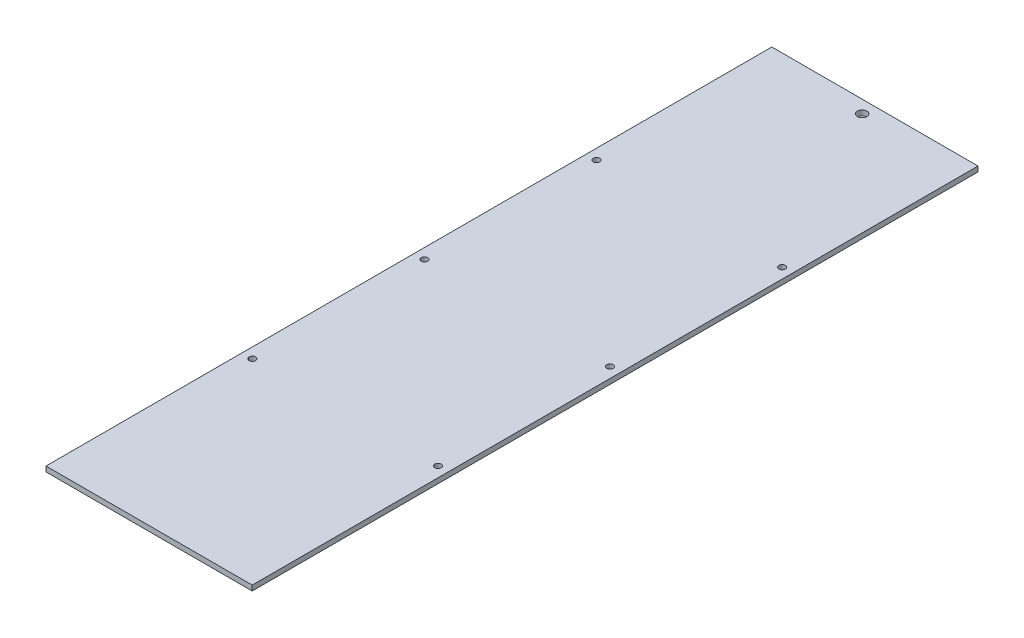
SolidWorks part; units mm, degrees
ref_plane "Front" through (0, 0, 0) normal (0, 0, 1) x (1, 0, 0)
ref_plane "Top" through (0, 0, 0) normal (0, 1, 0) x (1, 0, 0)
ref_plane "Right" through (0, 0, 0) normal (1, 0, 0) x (0, 0, -1)
sketch "Sketch1" plane through (0, 0, 0) normal (0, 1, 0) x (1, 0, 0)
  line L1 (-40, -140.81) -> (40, -140.81)
  line L2 (-40, -140.81) -> (-40, 140.81)
  line L3 (-40, 140.81) -> (40, 140.81)
  line L4 (40, -140.81) -> (40, 140.81)
  line L5 (-40, -140.81) -> (40, 140.81) construction
  line L6 (-40, 140.81) -> (40, -140.81) construction
  point P0 (0, 0)
  dimension "D1" = 281.62
  dimension "D2" = 80
extrude "Boss-Extrude1" add sketch "Sketch1" along normal blind 2
sketch "Sketch2" plane through (0, 2, 0) normal (0, 1, 0) x (1, 0, 0)
  line L0 (40, 140.81) -> (-40, 140.81) construction
  circle A0 centre (0, 135.87) radius 1.85
  dimension "D1" = 3.7
  dimension "D2" = 4.94
extrude "Cut-Extrude1" cut sketch "Sketch2" against normal blind 2
sketch "Sketch3" plane through (0, 2, 0) normal (0, 1, 0) x (1, 0, 0)
  line L0 (-40, 140.81) -> (-40, -140.81) construction
  line L1 (40, 140.81) -> (-40, 140.81) construction
  circle A0 centre (-36, 68.81) radius 1.25
  dimension "D1" = 2.5
  dimension "D2" = 4
  dimension "D3" = 72
extrude "Cut-Extrude2" cut sketch "Sketch3" against normal blind 2
pattern_linear "LPattern1" count 3 spacing 66.76 along (0, 0, 1) of "Cut-Extrude2"
mirror "Mirror1" about plane through (0, 0, 0) normal (1, 0, 0) of "LPattern1", "Cut-Extrude2"
